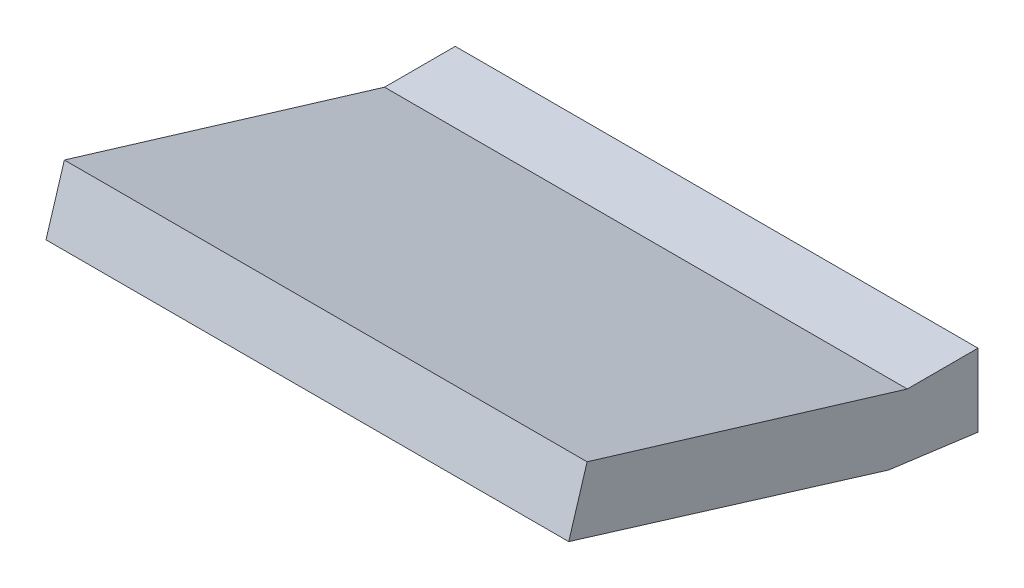
SolidWorks part; units mm, degrees
material "Polyurethane Foam Flexible"
ref_plane "Front Plane" through (0, 0, 0) normal (0, 0, 1) x (1, 0, 0)
ref_plane "Top Plane" through (0, 0, 0) normal (0, 1, 0) x (1, 0, 0)
ref_plane "Right Plane" through (0, 0, 0) normal (1, 0, 0) x (0, 0, -1)
sketch "Sketch1" plane through (0, 0, 0) normal (1, 0, 0) x (0, 0, -1)
  line L0 (0, 0) -> (-19.4466, 5.8935)
  line L1 (0, 0) -> (0, 12.1162)
  line L2 (-19.4466, 5.8935) -> (-20.5618, 2.2504)
  line L3 (-20.5618, 2.2504) -> (-1.1317, -3.6973)
  line L4 (0, 0) -> (-1.1317, -3.6973)
  dimension "D1" = 20.32
  dimension "D2" = 73.14
  dimension "D3" = 3.81
  dimension "D4" = 20.32
extrude "Boss-Extrude1" add sketch "Sketch1" along normal blind 31.75 contours L4 L3 L2 L0
sketch "Sketch2" plane through (0, 0, 0) normal (-1, 0, 0) x (0, 0, 1)
  line L0 (1.1317, -3.6973) -> (-4.2952, -3.6973)
  line L1 (-4.2952, -3.6973) -> (-4.2952, 0)
  line L2 (-4.2952, 0) -> (0, 0)
  line L3 (0, 0) -> (1.1317, -3.6973)
  line L7 (19.4466, 5.8935) -> (0, 0)
  line L8 (0, 0) -> (1.1317, -3.6973)
  line L9 (1.1317, -3.6973) -> (20.5618, 2.2504)
  line L10 (20.5618, 2.2504) -> (19.4466, 5.8935)
  line L11 (19.4466, 5.8935) -> (0, 0)
  line L13 (1.1317, -3.6973) -> (20.5618, 2.2504)
  line L14 (20.5618, 2.2504) -> (19.4466, 5.8935)
  line M9 (0, 0) -> (1.1317, -3.6973)
  dimension "D1" = 4.2952
  dimension "D2" = 0
extrude "Boss-Extrude2" add sketch "Sketch2" against normal blind 31.75 contours L2 L1 L0 M9
sketch "Sketch4" plane through (0, -3.6973, 0) normal (0, -1, 0) x (1, 0, 0)
  line L0 (0, -4.2952) -> (31.75, -4.2952)
  line L1 (0, -4.2952) -> (0, 3.4476)
  line L2 (31.75, -4.2952) -> (31.75, 3.4476)
  line L3 (0, 3.4476) -> (31.75, 3.4476)
extrude "Boss-Extrude3" add sketch "Sketch4" along normal blind 4.826
sketch "Sketch9" plane through (0, -8.5233, 0) normal (0, -1, 0) x (-1, 0, 0)
  line L0 (0, -3.4476) -> (0, 4.2952)
  line L1 (0, -3.4476) -> (-31.75, -3.4476)
  line L2 (0, 4.2952) -> (-31.75, 4.2952)
  line L3 (-31.75, -3.4476) -> (-31.75, 4.2952)
  dimension "D1" = 31.75
extrude "Cut-Extrude6" add sketch "Sketch9" along normal blind 1.772 contours L0 L1 L3 L2
sketch "Sketch10" plane through (0, 0, 0) normal (-1, 0, 0) x (0, 0, 1)
  line L0 (1.1317, -3.6973) -> (-4.2952, -4.421)
  line L1 (-4.2952, -6.7514) -> (-4.2952, 0) construction
  line L2 (-4.2952, -4.421) -> (-4.2952, -6.7514)
  line L3 (-4.2952, -6.7514) -> (3.4476, -6.7514)
  line L4 (3.4476, -6.7514) -> (3.4476, -3.6973)
  line L5 (3.4476, -3.6973) -> (1.1317, -3.6973)
extrude "Cut-Extrude7" cut sketch "Sketch10" against normal blind 39.116
